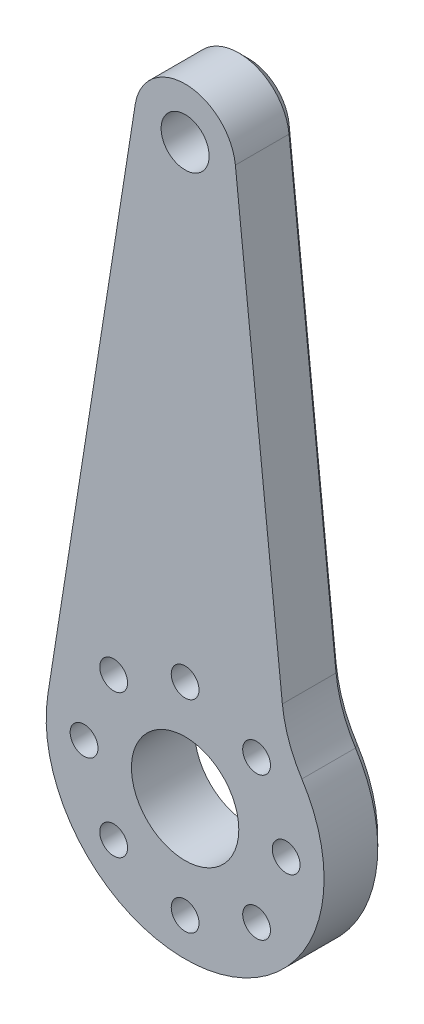
SolidWorks part; units mm, degrees
ref_plane "Front Plane" through (0, 0, 0) normal (0, 0, 1) x (1, 0, 0)
ref_plane "Top Plane" through (0, 0, 0) normal (0, 1, 0) x (1, 0, 0)
ref_plane "Right Plane" through (0, 0, 0) normal (1, 0, 0) x (0, 0, -1)
sketch "Sketch1" plane through (0, 0, 0) normal (0, 0, 1) x (1, 0, 0)
  line L0 (-18.9755, 25.4872) -> (-25.8903, -18.4239)
  line L3 (-11.0729, 25.4872) -> (-4.1581, -18.4239)
  line L4 (-15.0242, 0.8298) -> (-15.0242, 20.8298) construction
  line L5 (-14.673, -20.135) -> (49985.327, -20.135) construction
  circle A2 centre (-15.0242, 24.865) radius 1.9
  circle A3 centre (-15.0242, -20.135) radius 4.25
  arc A5 (-11.0729, 25.4872) -> (-18.9755, 25.4872) centre (-15.0242, 24.865) ccw
  arc A6 (-25.8903, -18.4239) -> (-4.1581, -18.4239) centre (-15.0242, -20.135) ccw
  circle A7 centre (-15.0314, -20.0888) radius 11 construction
  circle A8 centre (-7.0242, -20.135) radius 1.1
  circle A9 centre (-9.3674, -25.7919) radius 1.1
  circle A10 centre (-15.0242, -28.135) radius 1.1
  circle A11 centre (-20.6811, -25.7919) radius 1.1
  circle A12 centre (-23.0242, -20.135) radius 1.1
  circle A13 centre (-20.6811, -14.4782) radius 1.1
  circle A14 centre (-15.0242, -12.135) radius 1.1
  circle A15 centre (-9.3674, -14.4782) radius 1.1
  point P30 (-15.0242, -20.135)
  dimension "D1" = 3.8
  dimension "D3" = 45
  dimension "D4" = 11
  dimension "D2" = 4
  dimension "D5" = 8.5
  dimension "D6" = 2.2
  dimension "D7" = 8
  dimension "D8" = 8
extrude "Boss-Extrude1" add sketch "Sketch1" along normal blind 5
sketch "Sketch2" plane through (0, 0, 5) normal (0, 0, 1) x (1, 0, 0)
  circle A0 centre (-15.0242, -20.135) radius 11.5
  dimension "D1" = 23
extrude "Cut-Extrude1" [suppressed] cut sketch "Sketch2" against normal blind 1.75
sketch "Sketch5" plane through (0, 0, 5) normal (0, 0, 1) x (1, 0, 0)
  circle A2 centre (-14.8897, 3.8764) radius 1.55
  circle A3 centre (-14.8897, 3.8764) radius 8
extrude "Boss-Extrude2" [suppressed] add sketch "Sketch5" along normal blind 3
fillet "Fillet1" [suppressed] radius 1
sketch "Sketch4" plane through (0, 0, 0) normal (0, 0, -1) x (-1, 0, 0)
  circle A0 centre (23.0242, -20.135) radius 1.75
  circle A1 centre (20.6811, -25.7919) radius 1.75
  circle A2 centre (15.0242, -28.135) radius 1.75
  circle A3 centre (9.3674, -25.7919) radius 1.75
  circle A4 centre (7.0242, -20.135) radius 1.75
  circle A5 centre (9.3674, -14.4782) radius 1.75
  circle A6 centre (15.0242, -12.135) radius 1.75
  circle A7 centre (20.6811, -14.4782) radius 1.75
  circle A10 centre (15.0242, -20.135) radius 4.25 construction
  point P20 (15.0242, -20.135)
  dimension "D1" = 3.5
extrude "Cut-Extrude3" cut sketch "Sketch4" against normal blind 2.25
sketch "Croquis1" plane through (0, 0, 0) normal (0, 0, -1) x (-1, 0, 0)
  line L0 (11.0465, 25.2866) -> (7.0329, -12.576)
  line L1 (18.9755, 25.4872) -> (25.8903, -18.4239) construction
  line L2 (11.0729, 25.4872) -> (4.1581, -18.4239)
  arc A0 (11.0729, 25.4872) -> (11.0465, 25.2866) centre (15.0242, 24.865) ccw
  arc A1 (4.1581, -18.4239) -> (7.0329, -12.576) centre (15.0242, -20.135) cw
  dimension "D1" = 15
extrude "Cortar-Extruir1" cut sketch "Croquis1" against normal blind 10
fillet "Redondeo1" radius 10 1 edges at (-7.0329, -12.576, 2.5)
chamfer "Chaflán1" distance 0.75 angle 45 5 edges at (-22.4329, 3.5317, 0) (-12.746, -30.8965, 0) (-14.9231, 28.8637, 0) (-9.187, 7.7452, 0) (-6.8124, -12.0725, 0)
